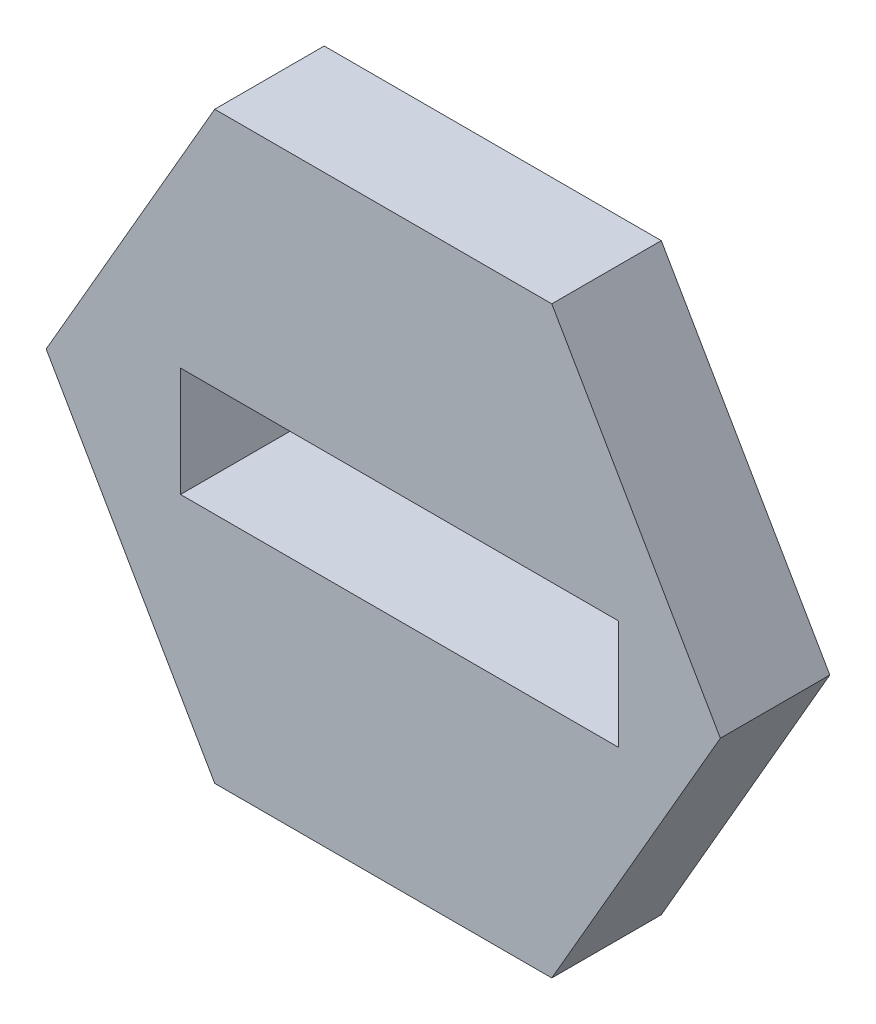
SolidWorks part; units mm, degrees
ref_plane "Front" through (0, 0, 0) normal (0, 0, 1) x (1, 0, 0)
ref_plane "Top" through (0, 0, 0) normal (0, 1, 0) x (1, 0, 0)
ref_plane "Right" through (0, 0, 0) normal (1, 0, 0) x (0, 0, -1)
sketch "Sketch1" plane through (0, 0, 0) normal (0, 0, 1) x (1, 0, 0)
  line L1 (-24.7918, 7.0834) -> (-12.7918, 7.0834)
  line L2 (-24.7918, 7.0834) -> (-24.7918, 4.0834)
  line L3 (-24.7918, 4.0834) -> (-12.7918, 4.0834)
  line L4 (-12.7918, 7.0834) -> (-12.7918, 4.0834)
  line L6 (-10.0018, 5.6948) -> (-14.6197, 13.6932)
  line L7 (-14.6197, 13.6932) -> (-23.8554, 13.6932)
  line L8 (-23.8554, 13.6932) -> (-28.4733, 5.6948)
  line L9 (-28.4733, 5.6948) -> (-23.8554, -2.3036)
  line L10 (-23.8554, -2.3036) -> (-14.6197, -2.3036)
  line L11 (-14.6197, -2.3036) -> (-10.0018, 5.6948)
  circle A0 centre (-19.2375, 5.6948) radius 7.9984 construction
  dimension "D1" = 12
  dimension "D2" = 3
extrude "Base-Extrude" add sketch "Sketch1" along normal blind 3
